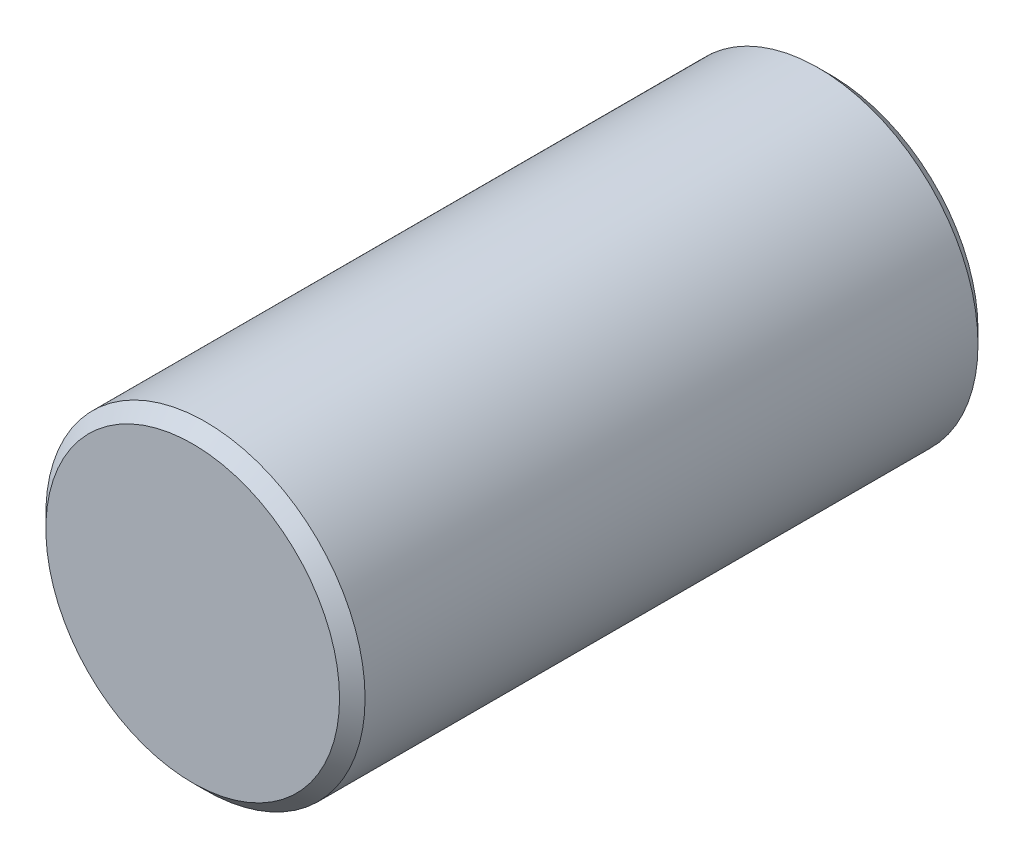
SolidWorks part; units mm, degrees
ref_plane "Front Plane" through (0, 0, 0) normal (0, 0, 1) x (1, 0, 0)
ref_plane "Top Plane" through (0, 0, 0) normal (0, 1, 0) x (1, 0, 0)
ref_plane "Right Plane" through (0, 0, 0) normal (1, 0, 0) x (0, 0, -1)
sketch "Sketch2" plane through (0, 0, 0) normal (0, 0, 1) x (1, 0, 0)
  circle A0 centre (0, 0) radius 1.25
  dimension "D1" = 2.5
extrude "Boss-Extrude1" add sketch "Sketch2" along normal mid plane 5
chamfer "Chamfer1" distance 0.1 angle 45 2 edges at (1.25, 0, -2.5) (1.25, 0, 2.5)
